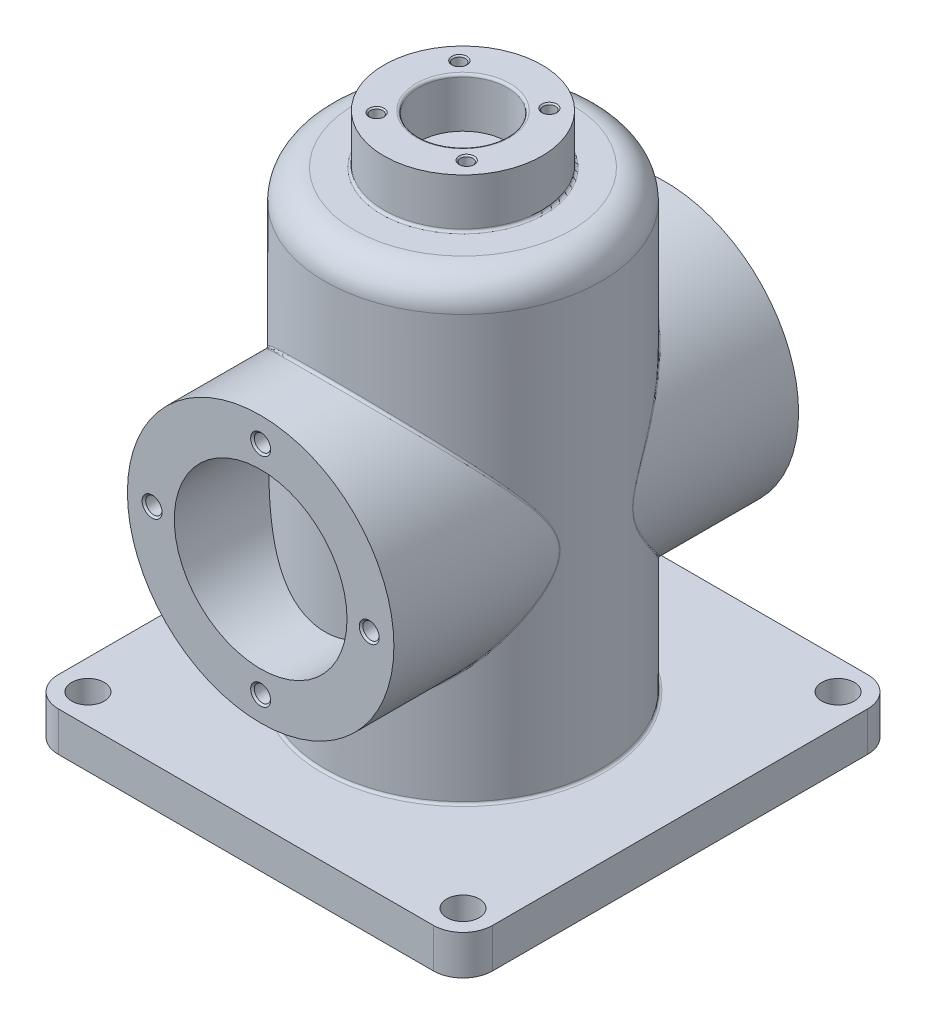
SolidWorks part; units mm, degrees
ref_plane "정면" through (0, 0, 0) normal (0, 0, 1) x (1, 0, 0)
ref_plane "윗면" through (0, 0, 0) normal (0, 1, 0) x (1, 0, 0)
ref_plane "우측면" through (0, 0, 0) normal (1, 0, 0) x (0, 0, -1)
sketch "스케치2" plane through (0, 0, 0) normal (0, 1, 0) x (1, 0, 0)
  line L1 (-44, 44) -> (44, 44)
  line L2 (-44, 44) -> (-44, -44)
  line L3 (-44, -44) -> (44, -44)
  line L4 (44, 44) -> (44, -44)
  line L5 (-44, 44) -> (44, -44) construction
  line L6 (-44, -44) -> (44, 44) construction
  point P0 (0, 0)
  dimension "D1" = 88
  dimension "D2" = 88
extrude "보스-돌출1" add sketch "스케치2" along normal blind 8
ref_plane "평면1" through (0, 0, 0) normal (0, 0, 1) x (1, 0, 0)
sketch "스케치5" plane through (0, 0, 0) normal (0, 0, 1) x (1, 0, 0)
  line L0 (0, -14.6837) -> (0, 107.7842) construction
  line L1 (0, 100) -> (-28, 100)
  line L2 (-28, 100) -> (-28, 8)
  line L3 (-28, 8) -> (0, 8)
  line L4 (0, 100) -> (0, 8)
  point P5 (0, 107.7842)
  dimension "D1" = 28
  dimension "D2" = 92
revolve "회전1" add sketch "스케치5" angle 360 about L0
sketch "스케치6" plane through (0, 8, 0) normal (0, 1, 0) x (1, 0, 0)
  circle A0 centre (0, 0) radius 23
  dimension "D1" = 46
extrude "컷-돌출1" cut sketch "스케치6" along normal blind 87
ref_plane "평면3" through (0, 0, 41) normal (0, 0, 1) x (1, 0, 0)
sketch "스케치8" plane through (0, 0, 41) normal (0, 0, 1) x (1, 0, 0)
  circle A0 centre (0, 50) radius 27
  circle A1 centre (0, 50) radius 17.5
  dimension "D1" = 54
  dimension "D2" = 35
  dimension "D3" = 50
extrude "보스-돌출2" add sketch "스케치8" against normal up to next
ref_plane "평면4" through (0, 0, 0) normal (0, 0, 1) x (1, 0, 0)
mirror "대칭 복사1" about plane through (0, 0, 0) normal (0, 0, 1) of "보스-돌출2"
ref_plane "평면5" through (0, 110, 0) normal (0, 1, 0) x (1, 0, 0)
sketch "스케치9" plane through (0, 110, 0) normal (0, 1, 0) x (1, 0, 0)
  circle A0 centre (0, 0) radius 16
  circle A1 centre (0, 0) radius 9
  dimension "D1" = 32
  dimension "D2" = 18
extrude "보스-돌출3" add sketch "스케치9" against normal up to next
fillet "필렛1" radius 6 1 edges at (0, 100, -28)
ref_plane "평면9" through (0, 0, 0) normal (1, 0, 0) x (0, 0, -1)
sketch "스케치12" plane through (0, 0, 0) normal (1, 0, 0) x (0, 0, -1)
  line L0 (-45.7012, 54.8361) -> (45.0563, 54.8361) construction
  line L3 (-28, 68.5) -> (-28, 41.5)
  arc A0 (-28, 68.5) -> (-28, 41.5) centre (-40.0995, 55) cw
  point P10 (-21.9708, 55)
  dimension "D1" = 27
  dimension "D2" = 55
ref_plane "평면10" through (0, 110, 0) normal (0, 1, 0) x (1, 0, 0)
sketch "스케치13" plane through (0, 110, 0) normal (0, 1, 0) x (1, 0, 0)
  point P0 (0, 0)
  point P1 (0, 0)
  point P8 (-9.1216, 8.3775)
hole_wizard "M3 나사 구멍2" positions "스케치17" profile "스케치16" tap size "M3" standard "KS"
sketch "스케치17" plane through (0, 110, 0) normal (0, 1, 0) x (1, 0, 0)
  point P0 (-9.1216, 8.3775)
sketch "스케치16" plane through (-9.1216, 110, -8.3775) normal (1, 0, 0) x (0, 0, 1)
  line L0 (0, 0) -> (0, 9.2511)
  line L1 (0, 9.2511) -> (1.25, 8.5)
  line L2 (1.25, 8.5) -> (1.25, 0.2656)
  line L3 (1.25, 0.2656) -> (1.525, 0)
  line L5 (1.525, 0) -> (0, 0)
  line L6 (-1.25, 0.2656) -> (-1.525, 0) construction
  line L10 (0, 9.2511) -> (-1.25, 8.5) construction
  line L11 (0, -6.35) -> (0, 107.95) construction
  dimension "탭 드릴 지름" = 2.5
  dimension "탭 드릴 깊이" = 8.5
  dimension "표면 카운터싱크 지름" = 3.05
  dimension "표면 카운터싱크 각도" = 92
  dimension "드릴 각도" = 118
cosmetic thread "구멍 나사산1" parameters "D1"=6, "D2"=3
pattern_circular "원형 패턴1" count 4 over 360 about axis through (0, 0, 0) along (0, 1, 0) of "M3 나사 구멍2"
cosmetic thread "구멍 나사산2" parameters "D1"=6, "D2"=3
cosmetic thread "구멍 나사산3" parameters "D1"=6, "D2"=3
cosmetic thread "구멍 나사산4" parameters "D1"=6, "D2"=3
sketch "스케치28" plane through (0, 0, 41) normal (0, 0, 1) x (1, 0, 0)
  circle A0 centre (0, 50) radius 22 construction
  point P3 (0, 72)
  dimension "D1" = 44
hole_wizard "M4 나사 구멍3" positions "3D스케치15" profile "스케치29" tap size "M4" standard "KS"
sketch3d "3D스케치15"
  point P0 (0, 72, 41)
sketch "스케치29" plane through (0, 72, 41) normal (1, 0, 0) x (0, -1, 0)
  line L0 (0, 0) -> (0, 12.4914)
  line L1 (0, 12.4914) -> (1.65, 11.5)
  line L2 (1.65, 11.5) -> (1.65, 0.3621)
  line L3 (1.65, 0.3621) -> (2.025, 0)
  line L5 (2.025, 0) -> (0, 0)
  line L6 (-1.65, 0.3621) -> (-2.025, 0) construction
  line L10 (0, 12.4914) -> (-1.65, 11.5) construction
  line L11 (0, -6.35) -> (0, 107.95) construction
  dimension "탭 드릴 지름" = 3.3
  dimension "탭 드릴 깊이" = 11.5
  dimension "표면 카운터싱크 지름" = 4.05
  dimension "표면 카운터싱크 각도" = 92
  dimension "드릴 각도" = 118
cosmetic thread "구멍 나사산5" parameters "D1"=8, "D2"=4
pattern_circular "원형 패턴2" count 4 over 360 about axis through (0, 50, 0) along (0, 0, 1) of "M4 나사 구멍3"
cosmetic thread "구멍 나사산6" parameters "D1"=8, "D2"=4
cosmetic thread "구멍 나사산7" parameters "D1"=8, "D2"=4
cosmetic thread "구멍 나사산8" parameters "D1"=8, "D2"=4
ref_plane "평면12" through (0, 0, 0) normal (0, 0, 1) x (1, 0, 0)
mirror "대칭 복사2" about plane through (0, 0, 0) normal (0, 0, 1) of "원형 패턴2", "M4 나사 구멍3"
cosmetic thread "구멍 나사산9" parameters "D1"=8, "D2"=4
cosmetic thread "구멍 나사산10" parameters "D1"=8, "D2"=4
cosmetic thread "구멍 나사산11" parameters "D1"=8, "D2"=4
cosmetic thread "구멍 나사산12" parameters "D1"=8, "D2"=4
fillet "필렛2" radius 6 4 edges at (-44, 4, -44) (44, 4, -44) (-44, 4, 44) (44, 4, 44)
ref_plane "평면13" through (0, 8, 0) normal (0, 1, 0) x (1, 0, 0)
sketch "스케치31" plane through (0, 8, 0) normal (0, 1, 0) x (1, 0, 0)
  circle A0 centre (-38, 38) radius 3.3
  dimension "D1" = 6.6
extrude "컷-돌출2" cut sketch "스케치31" against normal through all
pattern_linear "선형 패턴1" count 2 spacing 76 along (0, 0, 1) count 2 spacing 76 along (1, 0, 0) of "컷-돌출2"
fillet "필렛3" radius 0.5 5 edges at (0, 100, -16) (-2.257, 23.0945, -27.9089) (-26.9943, 50.5534, 7.4368) (0, 8, -28) (0, 110, 9)
